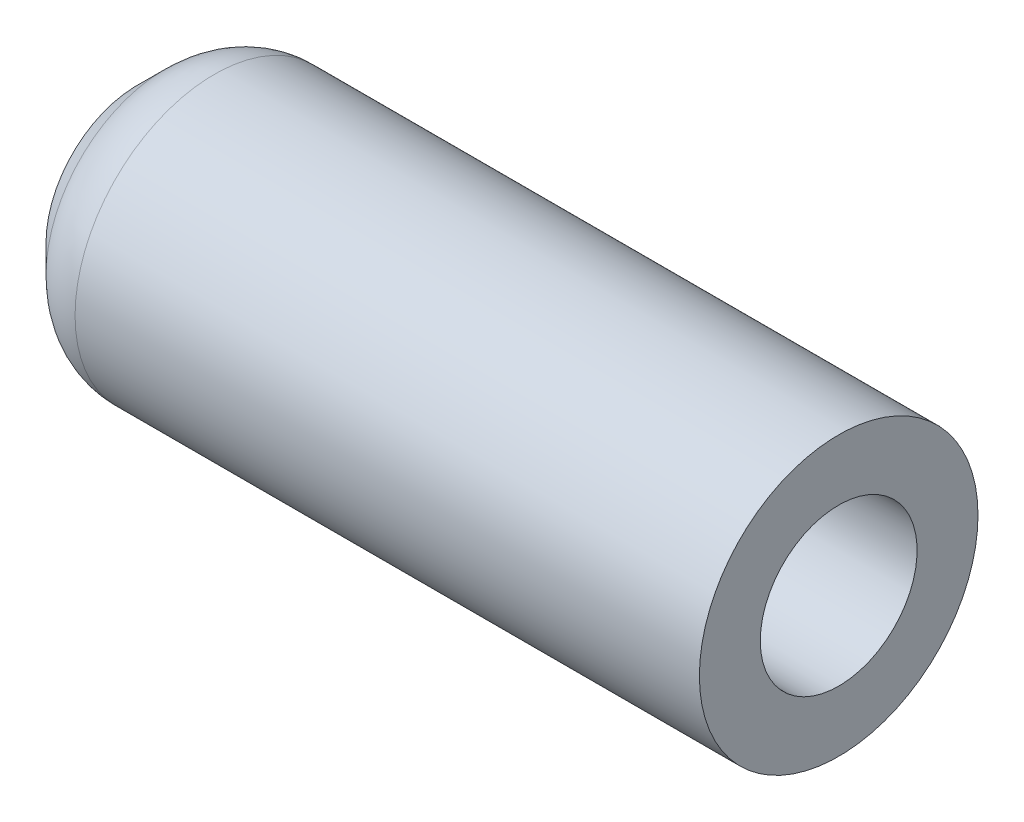
SolidWorks part; units mm, degrees
ref_plane "Front Plane" through (0, 0, 0) normal (0, 0, 1) x (1, 0, 0)
ref_plane "Top Plane" through (0, 0, 0) normal (0, 1, 0) x (1, 0, 0)
ref_plane "Right Plane" through (0, 0, 0) normal (1, 0, 0) x (0, 0, -1)
sketch "Sketch1" plane through (0, 0, 0) normal (0, 0, 1) x (1, 0, 0)
  line L0 (0, 0) -> (17.6646, 0) construction
  line L5 (0, 0) -> (0, 2.8)
  line L6 (0, 2.8) -> (1.4863, 4.2862)
  line L7 (1.4863, 4.2862) -> (21.59, 4.2862)
  line L8 (21.59, 4.2862) -> (21.59, 0)
  line L9 (21.59, 0) -> (0, 0)
  line L11 (0, 2.8) -> (-10.16, 2.8) construction
  line L12 (0, 2.8) -> (0, 0) construction
  line L13 (0, 0) -> (-10.16, 0) construction
  line L14 (-10.16, 2.8) -> (-10.16, 0) construction
  point P3 (-5.08, 2.8)
  dimension "D1" = 8.5725
  dimension "D2" = 5.6
  dimension "D3" = 135
  dimension "D4" = 10.16
  dimension "D5" = 26.67
revolve "Revolve1" add sketch "Sketch1" angle 360 about L0
sketch "Sketch2" plane through (0, 0, 0) normal (-1, 0, 0) x (0, 0, 1)
  circle A0 centre (0, 0) radius 2.0828
  dimension "D1" = 4.1656
fillet "Fillet1" radius 2.159 1 edges at (1.4863, 0, 4.2862)
sketch "Sketch3" plane through (0, 0, 0) normal (-1, 0, 0) x (0, 0, 1)
  circle A0 centre (0, 0) radius 2.413
  dimension "D1" = 4.826
extrude "Cut-Extrude1" cut sketch "Sketch3" against normal up to surface (21.59 mm away) up to face at (21.59, 0, 4.2862)
